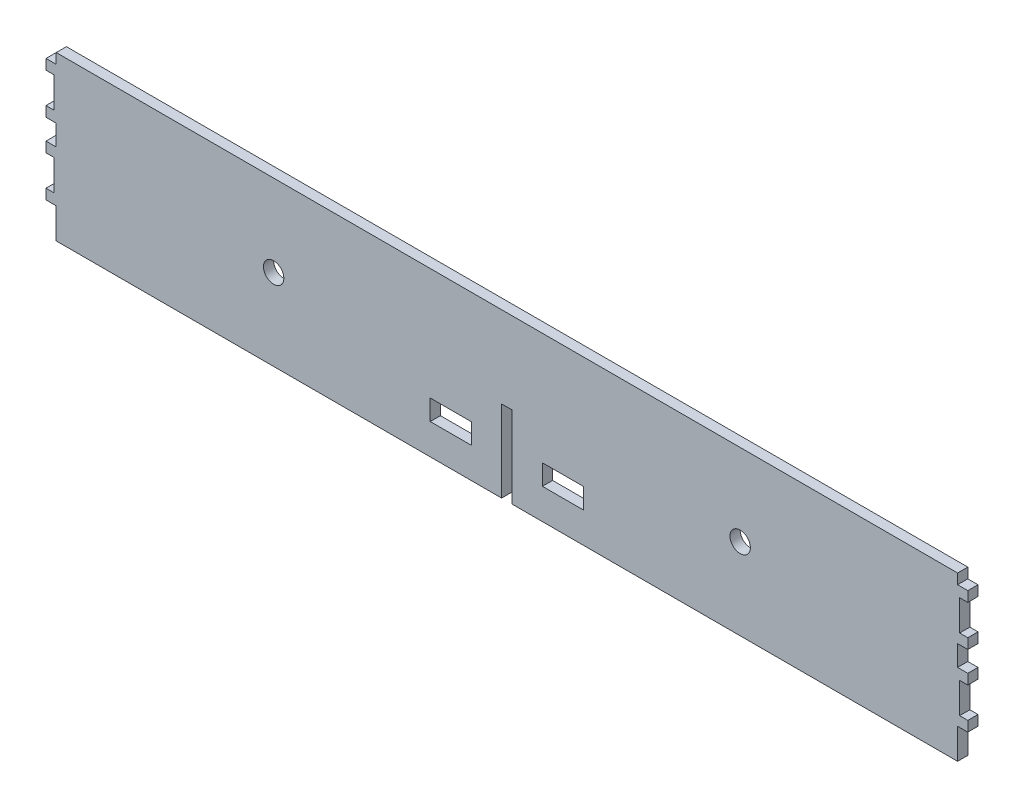
SolidWorks part; units mm, degrees
ref_plane "Front Plane" through (0, 0, 0) normal (0, 0, 1) x (1, 0, 0)
ref_plane "Top Plane" through (0, 0, 0) normal (0, 1, 0) x (1, 0, 0)
ref_plane "Right Plane" through (0, 0, 0) normal (1, 0, 0) x (0, 0, -1)
sketch "Sketch1" plane through (0, 0, 0) normal (0, 0, 1) x (1, 0, 0)
  line L1 (-221, 80) -> (221, 80)
  line L2 (-221, 80) -> (-221, 0)
  line L3 (-221, 0) -> (221, 0)
  line L4 (221, 80) -> (221, 0)
  point P4 (0, 0)
  dimension "D1" = 442
  dimension "D2" = 80
extrude "Boss-Extrude1" add sketch "Sketch1" along normal mid plane 5
sketch "Sketch4" plane through (0, 0, 2.5) normal (0, 0, 1) x (1, 0, 0)
  line L0 (-2.6, 0) -> (2.6, 0)
  line L1 (-2.6, 40) -> (2.6, 40)
  line L2 (-2.6, 40) -> (-2.6, 0)
  line L4 (2.6, 40) -> (2.6, 0)
  line L5 (-2.6, 40) -> (2.6, 0) construction
  line L6 (-2.6, 0) -> (2.6, 40) construction
  line L10 (2.75, 0) -> (-2.75, 0) construction
  point P0 (0, 20)
  dimension "D1" = 40
  dimension "D2" = 5.2
  dimension "D3" = 0
sketch "Sketch5" [suppressed] plane through (0, 0, 0) normal (0, 0, 1) x (1, 0, 0)
  line L0 (0, -2.75) -> (0, 2.75) construction
  line L1 (-65, -5) -> (-85, -5)
  line L2 (-65, -5) -> (-65, 5)
  line L3 (-65, 5) -> (-85, 5)
  line L4 (-85, -5) -> (-85, 5)
  line L5 (-65, -5) -> (-85, 5) construction
  line L6 (-65, 5) -> (-85, -5) construction
  line L7 (-215, -5) -> (-235, -5)
  line L8 (-215, -5) -> (-215, 5)
  line L9 (-215, 5) -> (-235, 5)
  line L10 (-235, -5) -> (-235, 5)
  line L11 (-215, -5) -> (-235, 5) construction
  line L12 (-215, 5) -> (-235, -5) construction
  line L13 (2.75, 0) -> (-2.75, 0) construction
  point P0 (-75, 0)
  point P5 (-225, 0)
  dimension "D1" = 75
  dimension "D2" = 150
  dimension "D3" = 10
  dimension "D4" = 20
sketch "Sketch2" plane through (0, 0, 0) normal (0, 0, 1) x (1, 0, 0)
  line L0 (-221, 0) -> (221, 0) construction
  line L1 (60, 0) -> (-60, 0)
  line L3 (55, 5) -> (-55, 5)
  arc A3 (-60, 0) -> (-55, 5) centre (-55, 0) cw
  arc A4 (55, 5) -> (60, 0) centre (55, 0) cw
  point P19 (0, 0)
  dimension "D3" = 5
  dimension "D6" = 5
extrude "Cut-Extrude1" [suppressed] cut sketch "Sketch2" along normal mid plane 5
sketch "Sketch7" plane through (221, 0, 0) normal (1, 0, 0) x (0, 0, -1)
  line L0 (-2.5, 0) -> (-2.5, 80) construction
  line L1 (-2.5, 75) -> (2.5, 75)
  line L2 (-2.5, 75) -> (-2.5, 50)
  line L3 (-2.5, 50) -> (2.5, 50)
  line L4 (2.5, 75) -> (2.5, 50)
  line L5 (2.5, 0) -> (2.5, 80) construction
  line L7 (-2.5, 39.9) -> (2.5, 39.9)
  line L8 (-2.5, 39.9) -> (-2.5, 14.9)
  line L9 (-2.5, 14.9) -> (2.5, 14.9)
  line L10 (2.5, 39.9) -> (2.5, 14.9)
  line L11 (-2.5, 80) -> (2.5, 80) construction
  line L14 (-2.6, 40) -> (2.4, 40) construction
  point P14 (0, 75)
  point P17 (0, 80)
  dimension "D1" = 0.1
  dimension "D2" = 25
  dimension "D3" = 25
  dimension "D4" = 5
extrude "Boss-Extrude2" add sketch "Sketch7" along normal blind 5
sketch "Sketch8" plane through (226, 0, 0) normal (1, 0, 0) x (0, 0, -1)
  line L0 (-2.5, 75) -> (-2.5, 50) construction
  line L1 (-2.5, 70) -> (2.5, 70)
  line L2 (-2.5, 70) -> (-2.5, 55)
  line L3 (-2.5, 55) -> (2.5, 55)
  line L4 (2.5, 70) -> (2.5, 55)
  line L5 (2.5, 50) -> (2.5, 75) construction
  line L6 (-2.5, 39.9) -> (-2.5, 14.9) construction
  line L7 (-2.5, 34.9) -> (2.5, 34.9)
  line L8 (-2.5, 34.9) -> (-2.5, 19.9)
  line L9 (-2.5, 19.9) -> (2.5, 19.9)
  line L10 (2.5, 34.9) -> (2.5, 19.9)
  line L11 (2.5, 14.9) -> (2.5, 39.9) construction
  line L12 (2.5, 75) -> (-2.5, 75) construction
  line L13 (-2.5, 50) -> (2.5, 50) construction
  line L14 (2.5, 39.9) -> (-2.5, 39.9) construction
  line L15 (-2.5, 14.9) -> (2.5, 14.9) construction
  point P20 (0, 50)
  dimension "D1" = 5
  dimension "D2" = 5
  dimension "D3" = 5
  dimension "D4" = 5
extrude "Cut-Extrude6" cut sketch "Sketch8" against normal blind 4
mirror "Mirror8" about plane through (0, 0, 0) normal (1, 0, 0) of "Cut-Extrude6", "Boss-Extrude2"
sketch "Sketch9" [suppressed] plane through (0, 0, 2.5) normal (0, 0, 1) x (1, 0, 0)
  line L0 (-315, 80) -> (-315, 75) construction
  line L1 (-315, 50) -> (-315, 40) construction
  line L2 (-315, 15) -> (-315, 10) construction
  line L3 (0, -2.75) -> (0, 2.75) construction
  circle A0 centre (-315, 76) radius 1
  circle A1 centre (-315, 49) radius 1
  circle A2 centre (-315, 41) radius 1
  circle A3 centre (-315, 14) radius 1
  circle A4 centre (315, 14) radius 1
  circle A5 centre (315, 41) radius 1
  circle A6 centre (315, 49) radius 1
  circle A7 centre (315, 76) radius 1
  dimension "D1" = 2
extrude "Cut-Extrude7" cut sketch "Sketch4" against normal blind 10
sketch "Sketch6" [suppressed] plane through (0, 0, 0) normal (0, 0, 1) x (1, 0, 0)
  line L0 (0, -2.75) -> (0, 2.75) construction
  line L1 (20.1, 40) -> (-20.1, 40)
  line L2 (20.1, 40) -> (20.1, 45.2)
  line L3 (20.1, 45.2) -> (-20.1, 45.2)
  line L4 (-20.1, 40) -> (-20.1, 45.2)
  line L5 (20.1, 40) -> (-20.1, 45.2) construction
  line L6 (20.1, 45.2) -> (-20.1, 40) construction
  line L7 (2.75, 0) -> (-2.75, 0) construction
  line L8 (170.1, 40) -> (129.9, 40)
  line L9 (170.1, 40) -> (170.1, 45.2)
  line L10 (170.1, 45.2) -> (129.9, 45.2)
  line L11 (129.9, 40) -> (129.9, 45.2)
  line L12 (170.1, 40) -> (129.9, 45.2) construction
  line L13 (170.1, 45.2) -> (129.9, 40) construction
  line L22 (-170.1, 45.2) -> (-129.9, 40) construction
  line L23 (-170.1, 40) -> (-129.9, 45.2) construction
  line L28 (-129.9, 40) -> (-129.9, 45.2)
  line L29 (-170.1, 45.2) -> (-129.9, 45.2)
  line L30 (-170.1, 40) -> (-170.1, 45.2)
  line L31 (-170.1, 40) -> (-129.9, 40)
  line L32 (320.1, 40) -> (279.9, 40) [skipped]
  line L33 (320.1, 40) -> (320.1, 45.2) [skipped]
  line L34 (320.1, 45.2) -> (279.9, 45.2) [skipped]
  line L35 (279.9, 40) -> (279.9, 45.2) [skipped]
  line L36 (320.1, 40) -> (279.9, 45.2) construction
  line L37 (320.1, 45.2) -> (279.9, 40) construction
  point P0 (0, 42.6)
  point P5 (300, 42.6)
  point P8 (0, 40)
  point P12 (150, 42.6)
  point P29 (-150, 42.6)
  dimension "D1" = 40.2
  dimension "D2" = 5.2
  dimension "D3" = 40
  dimension "D5" = 150
  dimension "D4" = 3
extrude "Cut-Extrude8" cut sketch "Sketch10" against normal blind 300
sketch "Sketch10" plane through (0, -565.4562, -2.5) normal (0, 0, -1) x (-1, 0, 0)
  line L4 (17.4, 590.4562) -> (37.6, 590.4562)
  line L5 (37.6, 590.4562) -> (37.6, 580.4562)
  line L6 (17.4, 580.4562) -> (37.6, 580.4562)
  line L7 (17.4, 590.4562) -> (17.4, 580.4562)
mirror "Mirror9" about plane through (0, 0, 0) normal (1, 0, 0) of "Cut-Extrude8"
sketch "Sketch11" plane through (0, 0, -2.5) normal (0, 0, -1) x (-1, 0, 0)
  line L0 (663, 39.9) -> (-221, 39.9) construction
  line L3 (0, 2.75) -> (0, -2.75) construction
  circle A2 centre (-114.3852, 39.9) radius 5
  circle A3 centre (114.3852, 39.9) radius 5
  point P4 (221, 39.9)
extrude "Cut-Extrude9" cut sketch "Sketch11" against normal blind 10
